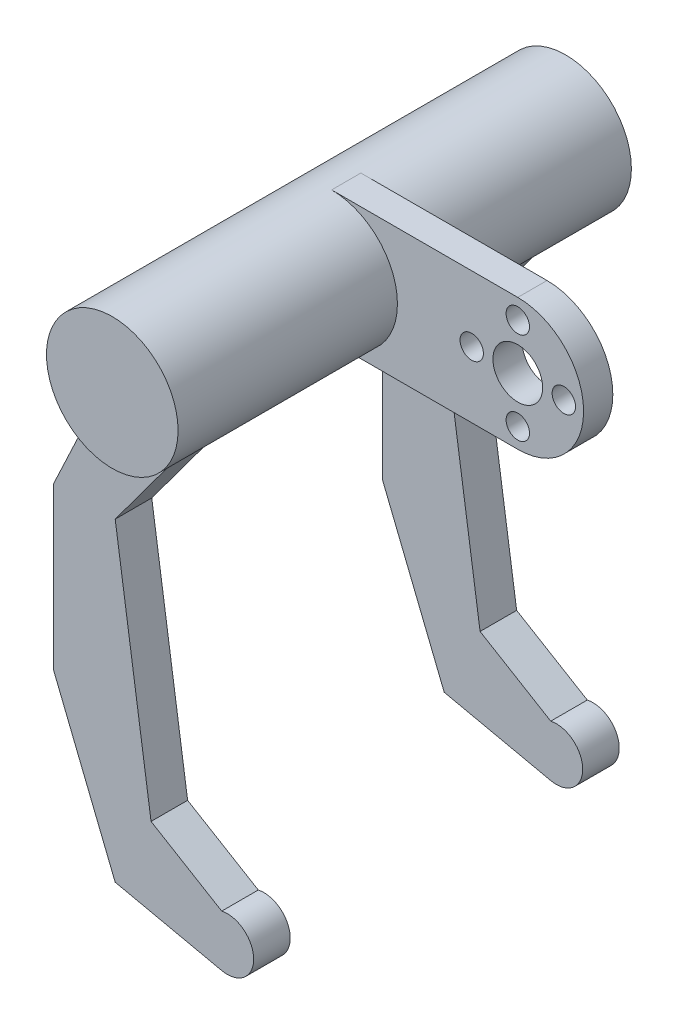
SolidWorks part; units mm, degrees
ref_plane "Front Plane" through (0, 0, 0) normal (0, 0, 1) x (1, 0, 0)
ref_plane "Top Plane" through (0, 0, 0) normal (0, 1, 0) x (1, 0, 0)
ref_plane "Right Plane" through (0, 0, 0) normal (1, 0, 0) x (0, 0, -1)
sketch "Sketch2" plane through (0, 0, 0) normal (0, 0, 1) x (1, 0, 0)
  circle A0 centre (0, 0) radius 11.43
  dimension "D1" = 22.86
extrude "Boss-Extrude1" add sketch "Sketch2" along normal blind 5.08
sketch "Sketch7" plane through (0, 0, 0) normal (0, 0, -1) x (-1, 0, 0)
  line L1 (0, 11.43) -> (32.3349, 11.43)
  line L2 (0, 11.43) -> (0, -11.43)
  line L3 (0, -11.43) -> (32.3349, -11.43)
  circle A1 centre (0, 0) radius 11.43 construction
  arc A2 (32.3349, 11.43) -> (32.3349, -11.43) centre (32.3349, 0) cw
extrude "Boss-Extrude2" add sketch "Sketch7" against normal blind 5.08
ref_plane "Plane1" through (0, 0, -31.75) normal (0, 0, 1) x (1, 0, 0)
sketch "Sketch4" plane through (0, 0, 0) normal (0, 0, -1) x (-1, 0, 0)
  circle A0 centre (0, 0) radius 4.318
  circle A1 centre (0, -8.001) radius 2.032
  dimension "D1" = 8.001
extrude "Cut-Extrude1" cut sketch "Sketch4" against normal blind 5.08
pattern_circular "CirPattern1" count 4 over 360 about axis through (0, 0, 0) along (0, 0, 1) of "Cut-Extrude1"
ref_plane "Plane2" through (-27.94, 0, 0) normal (1, 0, 0) x (0, 0, -1)
sketch "Sketch9" plane through (0, 0, 5.08) normal (0, 0, 1) x (1, 0, 0)
  circle A0 centre (-32.3349, 0) radius 11.43
extrude "Boss-Extrude3" add sketch "Sketch9" along normal blind 38.1 and the other way blind 40.64
sketch "Sketch10" plane through (0, 0, -31.75) normal (0, 0, 1) x (1, 0, 0)
  line L0 (-43.2583, -30.2196) -> (-20.9049, 0)
  line L1 (-39.7308, 0.0259) -> (-53.9503, -30.2196)
  line L2 (-53.9503, -58.3083) -> (-43.2583, -84.8421)
  line L3 (-43.2583, -84.8421) -> (-24.7566, -88.8741)
  line L4 (-24.7566, -79.9341) -> (-37.0287, -72.5822)
  line L5 (-37.0287, -72.5822) -> (-43.2583, -30.2196)
  line L6 (-53.9503, -30.2196) -> (-53.9503, -58.3083)
  line L7 (-20.9049, 0) -> (-39.7308, 0.0259)
  line L9 (-32.0617, 0.0259) -> (-32.3349, 0)
  arc A0 (-24.7566, -88.8741) -> (-24.7566, -79.9341) centre (-23.7825, -84.4041) ccw
  arc A1 (-32.3349, -11.43) -> (-32.3349, 11.43) centre (-32.3349, 0) ccw construction
extrude "Boss-Extrude4" add sketch "Sketch10" along normal blind 6.35
mirror "Mirror1" about plane through (0, 0, 0) normal (0, 0, 1) of "Boss-Extrude4"
